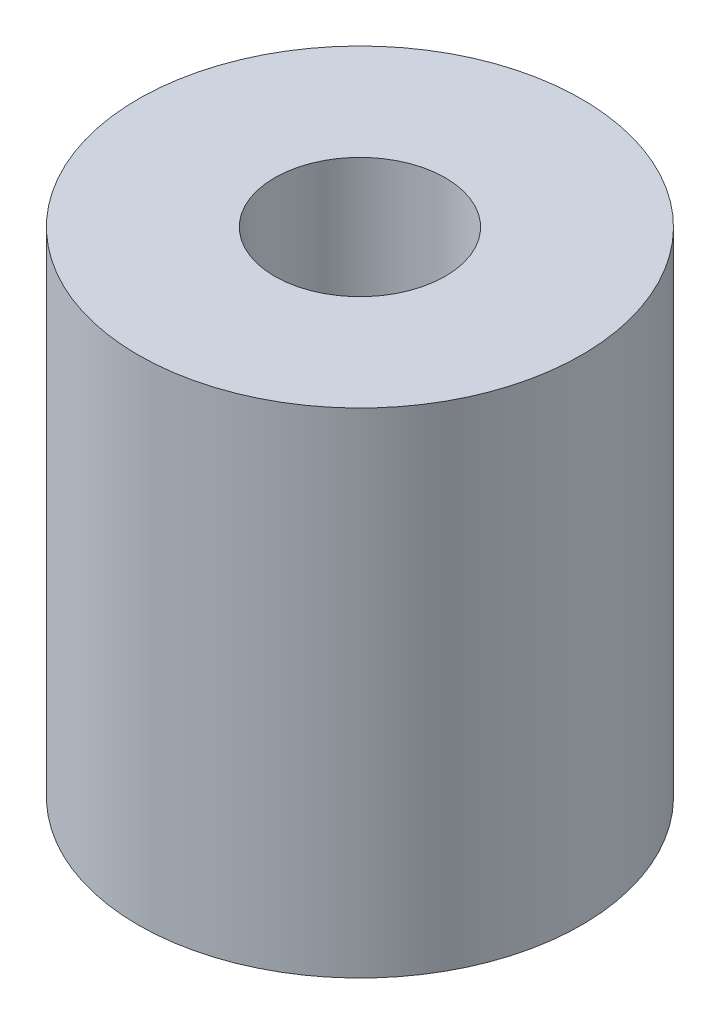
SolidWorks part; units mm, degrees
ref_plane "Front Plane" through (0, 0, 0) normal (0, 0, 1) x (1, 0, 0)
ref_plane "Top Plane" through (0, 0, 0) normal (0, 1, 0) x (1, 0, 0)
ref_plane "Right Plane" through (0, 0, 0) normal (1, 0, 0) x (0, 0, -1)
sketch "Sketch1" plane through (0, 0, 0) normal (0, 1, 0) x (1, 0, 0)
  circle A0 centre (0, 0) radius 5
  circle A1 centre (0, 0) radius 1.575
  dimension "D1" = 10
  dimension "D2" = 3.15
extrude "Boss-Extrude1" add sketch "Sketch1" along normal blind 11.132
sketch "Sketch2" plane through (0, 11.132, 0) normal (0, 1, 0) x (1, 0, 0)
  circle A0 centre (0, 0) radius 1.925
  dimension "D1" = 3.85
extrude "Cut-Extrude1" cut sketch "Sketch2" against normal blind 4
equation "\"D1@Boss-Extrude1\"=\"sheetThickness\"*2+0.5*\"ballBearDiam\""
equation "\"largeBearOD\"= 21mm"
equation "\"largeBearID\" = 15mm"
equation "\"largeBearOTight\"= 0.127mm'calibrate - hold onto gears"
equation "\"largeBearITight\"= 0mm'calibrate - hold onto eccentric nut"
equation "\"largeBearFlangeDiam\" = 22.5mm"
equation "\"largeBearFlangeWidth\" = 0.8mm"
equation "\"smallBearOD\"= 15mm"
equation "\"smallBearOTight\"= 0mm'calibrate - hold onto bottom of gearbox"
equation "\"smallBearOLoose\"= 0mm'calibrate - able to take off topHat"
equation "\"smallBearID\" = 10mm"
equation "\"smallBearITight\" = 0mm'hold onto "
equation "\"pinCircleDiam\"= 75mm"
equation "\"pinDiam\"= 6mm"
equation "\"sheetThickness\"= 0.1875in"
equation "\"ballBearDiam\"= 3.214mm"
equation "\"thrustBearingThickness\"= 5mm'measure this irl and change"
equation "\"thrustBearingID\"= 0mm'measure this irl and change"
equation "\"thrustBearingOD\"= 0mm'measure this irl and change"
equation "\"eccentricity\" = 1mm"
